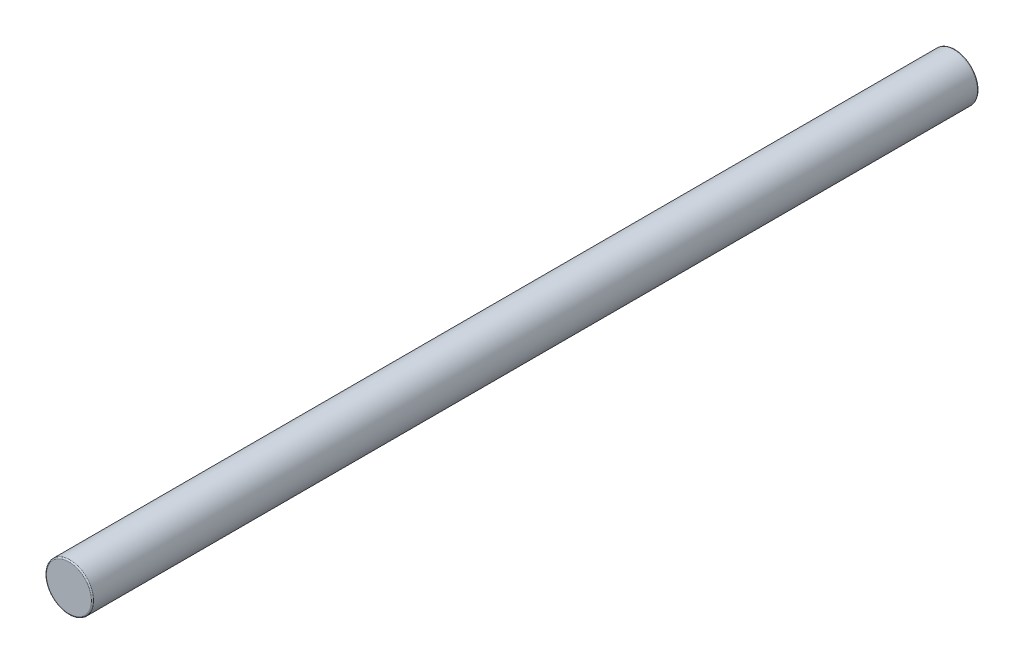
SolidWorks part; units mm, degrees
ref_plane "Front" through (0, 0, 0) normal (0, 0, 1) x (1, 0, 0)
ref_plane "Top" through (0, 0, 0) normal (0, 1, 0) x (1, 0, 0)
ref_plane "Right" through (0, 0, 0) normal (1, 0, 0) x (0, 0, -1)
sketch "Sketch1" plane through (0, 0, 0) normal (0, 0, 1) x (1, 0, 0)
  circle A0 centre (0, 0) radius 4
  dimension "D1" = 8
extrude "Boss-Extrude1" add sketch "Sketch1" against normal blind 150
fillet "Fillet1" radius 0.2 2 edges at (4, 0, 0) (4, 0, -150)
